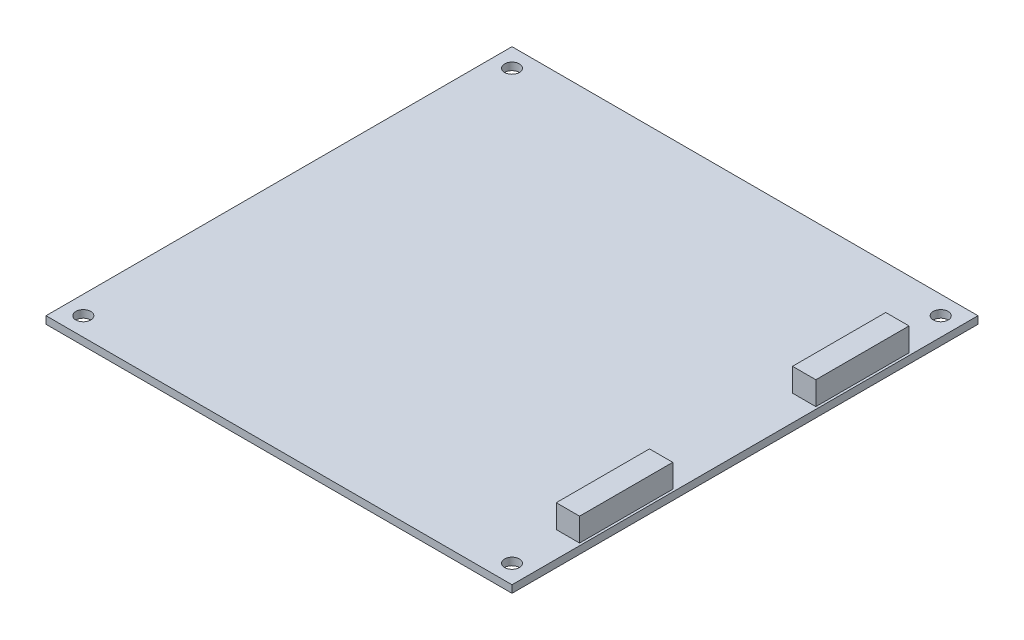
SolidWorks part; units mm, degrees
ref_plane "Front Plane" through (0, 0, 0) normal (0, 0, 1) x (1, 0, 0)
ref_plane "Top Plane" through (0, 0, 0) normal (0, 1, 0) x (1, 0, 0)
ref_plane "Right Plane" through (0, 0, 0) normal (1, 0, 0) x (0, 0, -1)
sketch "Sketch1" plane through (0, 0, 0) normal (0, 1, 0) x (1, 0, 0)
  line L1 (-50, 50) -> (50, 50)
  line L2 (-50, 50) -> (-50, -50)
  line L3 (-50, -50) -> (50, -50)
  line L4 (50, 50) -> (50, -50)
  line L5 (-50, 50) -> (50, -50) construction
  line L6 (-50, -50) -> (50, 50) construction
  point P0 (0, 0)
  dimension "D1" = 100
extrude "Boss-Extrude1" add sketch "Sketch1" along normal blind 1.6
sketch "Sketch2" plane through (0, 1.6, 0) normal (0, 1, 0) x (1, 0, 0)
  line L0 (-50, 50) -> (-50, -50) construction
  line L1 (-46, 46) -> (46, 46) construction
  line L2 (-46, 46) -> (-46, -46) construction
  line L3 (-46, -46) -> (46, -46) construction
  line L4 (46, 46) -> (46, -46) construction
  line L5 (-46, 46) -> (46, -46) construction
  line L6 (-46, -46) -> (46, 46) construction
  line L7 (-50, -50) -> (50, -50) construction
  circle A0 centre (-46, -46) radius 1.6
  circle A1 centre (-46, 46) radius 1.6
  circle A2 centre (46, 46) radius 1.6
  circle A3 centre (46, -46) radius 1.6
  point P0 (0, 0)
  dimension "D3" = 3.2
  dimension "D1" = 4
  dimension "D2" = 4
extrude "Cut-Extrude1" cut sketch "Sketch2" against normal through all
sketch "Sketch3" plane through (0, 1.6, 0) normal (0, 1, 0) x (1, 0, 0)
  line L0 (47, 50) -> (47, -50) construction
  line L1 (50, 50) -> (-50, 50) construction
  line L2 (-50, -50) -> (50, -50) construction
  line L3 (50, -50) -> (50, 50) construction
  line L4 (44.5, -15) -> (49.5, -15)
  line L5 (44.5, -15) -> (44.5, -35)
  line L6 (44.5, -35) -> (49.5, -35)
  line L7 (49.5, -15) -> (49.5, -35)
  line L8 (44.5, -15) -> (49.5, -35) construction
  line L9 (44.5, -35) -> (49.5, -15) construction
  line L10 (49.5, 35.7) -> (44.5, 35.7)
  line L11 (49.5, 35.7) -> (49.5, 15.7)
  line L12 (49.5, 15.7) -> (44.5, 15.7)
  line L13 (44.5, 35.7) -> (44.5, 15.7)
  line L14 (49.5, 35.7) -> (44.5, 15.7) construction
  line L15 (49.5, 15.7) -> (44.5, 35.7) construction
  point P6 (47, -25)
  point P11 (47, 25.7)
  dimension "D1" = 25
  dimension "D2" = 75.7
  dimension "D3" = 20
  dimension "D4" = 5
  dimension "D5" = 3
extrude "Boss-Extrude2" add sketch "Sketch3" along normal blind 5
